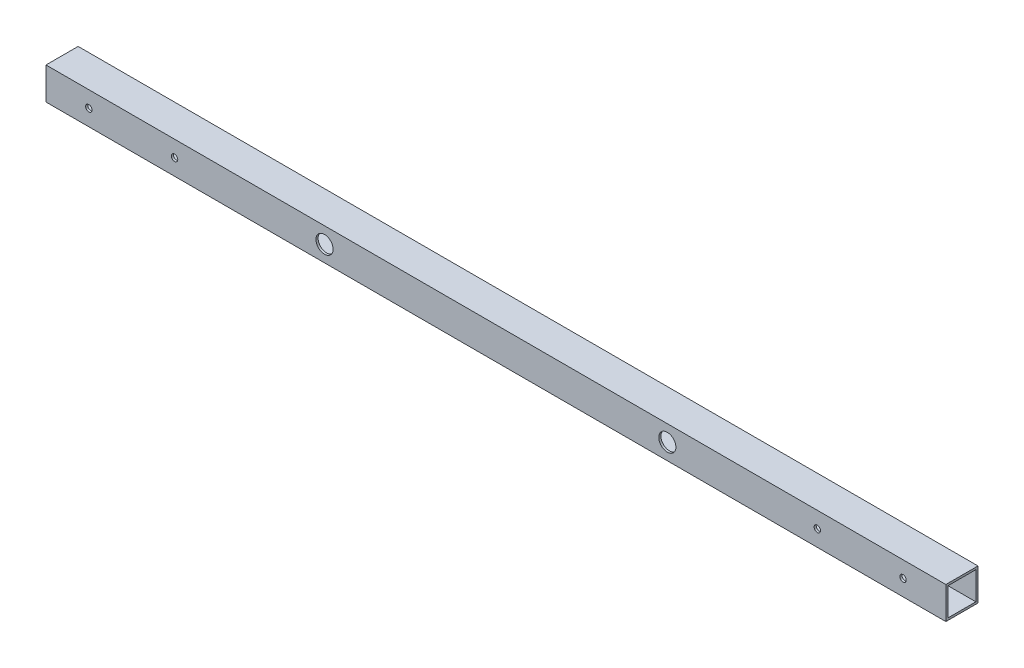
SolidWorks part; units mm, degrees
ref_plane "前视基准面" through (0, 0, 0) normal (0, 0, 1) x (1, 0, 0)
ref_plane "上视基准面" through (0, 0, 0) normal (0, 1, 0) x (1, 0, 0)
ref_plane "右视基准面" through (0, 0, 0) normal (1, 0, 0) x (0, 0, -1)
sketch "草图1" plane through (0, 0, 0) normal (1, 0, 0) x (0, 0, -1)
  line L0 (-6.5, 6.5) -> (6.5, 6.5)
  line L1 (-7.5, -7.5) -> (7.5, -7.5)
  line L2 (-7.5, -7.5) -> (-7.5, 7.5)
  line L3 (-7.5, 7.5) -> (7.5, 7.5)
  line L4 (7.5, -7.5) -> (7.5, 7.5)
  line L5 (-7.5, -7.5) -> (7.5, 7.5) construction
  line L6 (-7.5, 7.5) -> (7.5, -7.5) construction
  line L7 (6.5, -6.5) -> (6.5, 6.5)
  line L8 (-6.5, -6.5) -> (6.5, -6.5)
  line L9 (-6.5, -6.5) -> (-6.5, 6.5)
  point P0 (0, 0)
  dimension "D1" = 15
  dimension "D2" = 15
  dimension "D3" = 1
extrude "凸台-拉伸1" add sketch "草图1" along normal blind 420
sketch "草图2" plane through (0, 0, 7.5) normal (0, 0, 1) x (1, 0, 0)
  line L0 (0, 7.5) -> (0, -7.5) construction
  line L1 (210, 27.061) -> (210, -47.3353) construction
  circle A0 centre (20, 0) radius 1.5
  circle A1 centre (60, 0) radius 1.5
  circle A2 centre (130, 0) radius 1.5
  circle A3 centre (290, 0) radius 1.5
  circle A4 centre (360, 0) radius 1.5
  circle A5 centre (400, 0) radius 1.5
  dimension "D1" = 20
  dimension "D2" = 60
  dimension "D3" = 130
extrude "切除-拉伸1" cut sketch "草图2" against normal through all
sketch "草图3" plane through (0, 0, 7.5) normal (0, 0, 1) x (1, 0, 0)
  circle A0 centre (130, 0) radius 4
  circle A1 centre (290, 0) radius 4
extrude "切除-拉伸2" cut sketch "草图3" against normal blind 10
